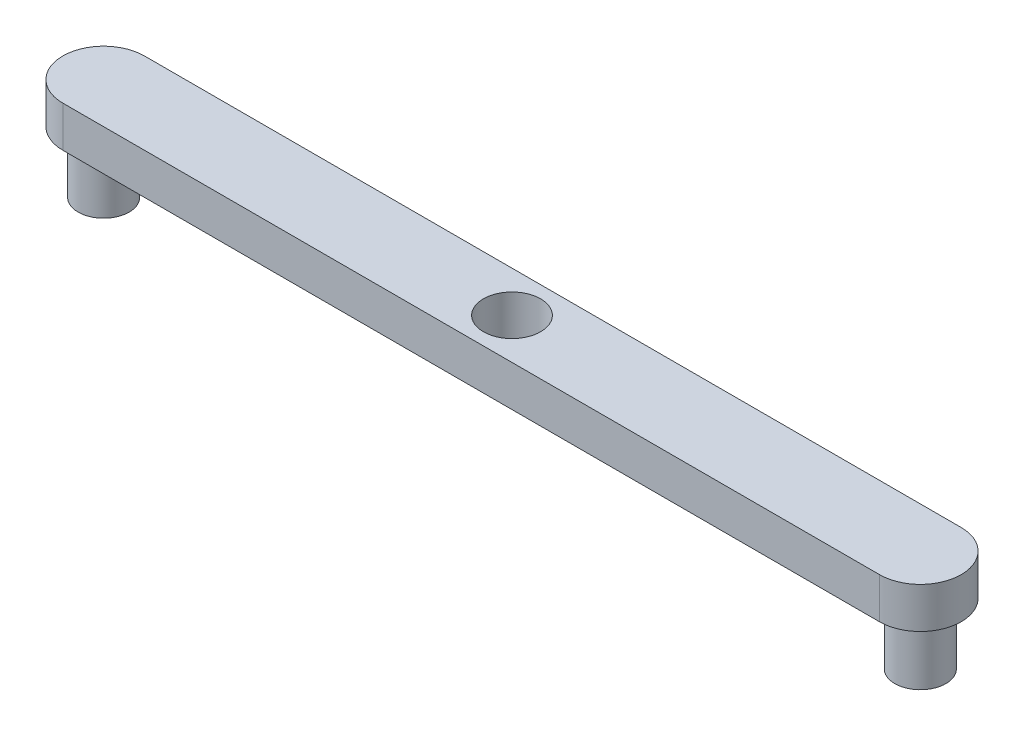
SolidWorks part; units mm, degrees
ref_plane "Front Plane" through (0, 0, 0) normal (0, 0, 1) x (1, 0, 0)
ref_plane "Top Plane" through (0, 0, 0) normal (0, 1, 0) x (1, 0, 0)
ref_plane "Right Plane" through (0, 0, 0) normal (1, 0, 0) x (0, 0, -1)
sketch "Sketch1" plane through (0, 0, 0) normal (0, 1, 0) x (1, 0, 0)
  line L0 (0, 0) -> (-50.8, 0)
  line L1 (0, 0) -> (50.8, 0)
  line L2 (-50.8, -5.08) -> (50.8, -5.08)
  line L3 (-50.8, 5.08) -> (50.8, 5.08)
  arc A0 (-50.8, 5.08) -> (-50.8, -5.08) centre (-50.8, 0) ccw
  arc A1 (50.8, -5.08) -> (50.8, 5.08) centre (50.8, 0) ccw
  dimension "D1" = 101.6
sketch "Sketch2" plane through (0, 0, 0) normal (0, 1, 0) x (1, 0, 0)
  line L0 (-50.8, -5.08) -> (50.8, -5.08)
  line L1 (-50.8, 5.08) -> (50.8, 5.08)
  arc A0 (-50.8, 5.08) -> (-50.8, -5.08) centre (-50.8, 0) ccw
  arc A1 (50.8, -5.08) -> (50.8, 5.08) centre (50.8, 0) ccw
extrude "Boss-Extrude1" add sketch "Sketch2" along normal blind 5.08
sketch "Sketch3" plane through (0, 0, 0) normal (0, -1, 0) x (1, 0, 0)
  circle A0 centre (-50.8, 0) radius 3.175
  circle A1 centre (50.8, 0) radius 3.175
extrude "Boss-Extrude2" add sketch "Sketch3" along normal blind 7.62
sketch "Sketch4" plane through (0, -7.62, 0) normal (0, -1, 0) x (1, 0, 0)
  circle A0 centre (-50.8, 0) radius 5.08
  circle A1 centre (50.8, 0) radius 5.08
sketch "Sketch5" plane through (0, 0, 0) normal (0, 1, 0) x (1, 0, 0)
  circle A0 centre (0, 0) radius 3.302
sketch "Sketch7" plane through (0, 0, 0) normal (0, 1, 0) x (1, 0, 0)
  circle A0 centre (0, 0) radius 3.556
extrude "Cut-Extrude1" cut sketch "Sketch7" along normal up to vertex (5.08 mm away)
